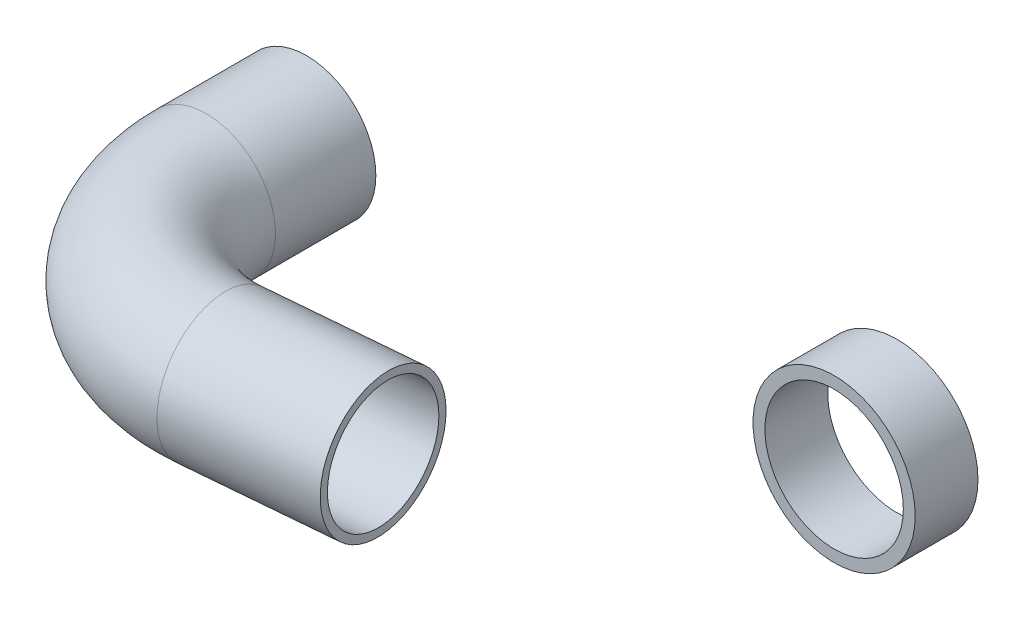
SolidWorks part; units mm, degrees
material "AISI 321 Annealed Stainless Steel (SS)"
ref_plane "Front Plane" through (0, 0, 0) normal (0, 0, 1) x (1, 0, 0)
ref_plane "Top Plane" through (0, 0, 0) normal (0, 1, 0) x (1, 0, 0)
ref_plane "Right Plane" through (0, 0, 0) normal (1, 0, 0) x (0, 0, -1)
sketch "Sketch1" plane through (0, 0, 0) normal (0, 0, 1) x (1, 0, 0)
  circle A0 centre (0, 0) radius 20.5
  circle A1 centre (0, 0) radius 17.5
  dimension "D1" = 41
  dimension "D2" = 3
extrude "Boss-Extrude1" add sketch "Sketch1" along normal blind 15.875
ref_plane "Plane1" through (0, 0, 9.525) normal (0, 0, 1) x (1, 0, 0)
sketch "Sketch2" plane through (0, 0, 9.525) normal (0, 0, 1) x (1, 0, 0)
  circle A0 centre (0, 0) radius 17.5
  circle A1 centre (0, 0) radius 15.5
  dimension "D1" = 2
  dimension "D2" = 35
sketch "Sketch4" plane through (0, 0, 9.525) normal (0, 0, 1) x (1, 0, 0)
  line L0 (0, 0) -> (-161.9875, 0) construction
  circle A0 centre (-139.7, 0) radius 17.5
  circle A1 centre (-139.7, 0) radius 15.5
  dimension "D1" = 35
  dimension "D2" = 2
  dimension "D7" = 139.7
sketch "Sketch5" plane through (0, 0, 0) normal (0, 1, 0) x (1, 0, 0)
  line L2 (-60.3243, -69.5594) -> (-98.2794, -72.88)
  line L3 (-139.7, -34.925) -> (-139.7, -9.525)
  line L4 (-155.2, -9.525) -> (-124.2, -9.525) construction
  line L5 (0, -9.525) -> (-161.9875, -9.525) construction
  arc A1 (-98.2794, -72.88) -> (-139.7, -34.925) centre (-101.6, -34.925) cw
  dimension "D2" = 85
  dimension "D3" = 38.1
  dimension "D1" = 38.1
sweep "Sweep1" add profiles "Sketch4" path "Sketch5"
